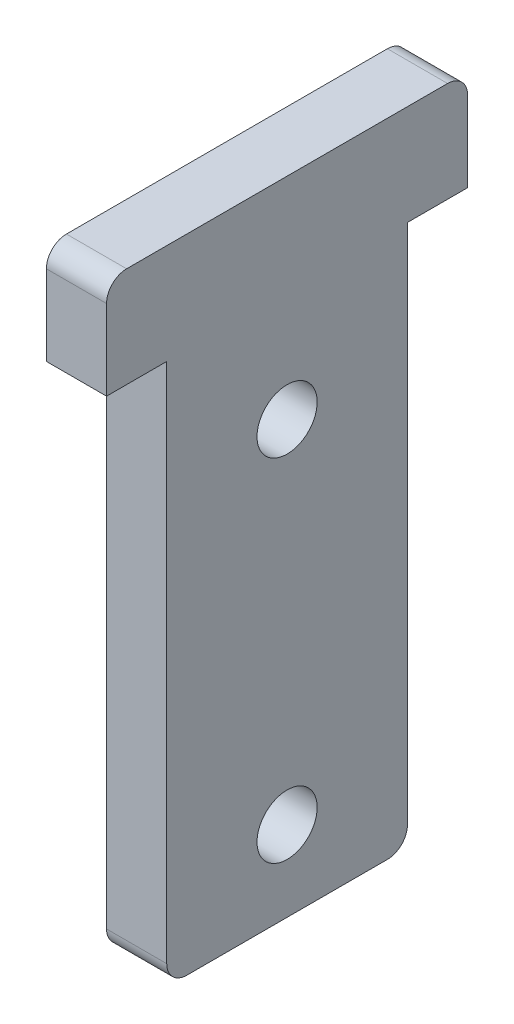
SolidWorks part; units mm, degrees
ref_plane "Front Plane" through (0, 0, 0) normal (0, 0, 1) x (1, 0, 0)
ref_plane "Top Plane" through (0, 0, 0) normal (0, 1, 0) x (1, 0, 0)
ref_plane "Right Plane" through (0, 0, 0) normal (1, 0, 0) x (0, 0, -1)
sketch "Sketch1" plane through (0, 0, 0) normal (1, 0, 0) x (0, 0, -1)
  line L1 (9, -16) -> (-9, -16)
  line L2 (9, -16) -> (9, 16)
  line L3 (9, 16) -> (-9, 16)
  line L4 (-9, -16) -> (-9, 16)
  line L5 (9, -16) -> (-9, 16) construction
  line L6 (9, 16) -> (-9, -16) construction
  point P0 (0, 0)
  dimension "D1" = 18
  dimension "D2" = 32
extrude "Boss-Extrude1" add sketch "Sketch1" along normal blind 3
sketch "Sketch2" plane through (3, 0, 0) normal (1, 0, 0) x (0, 0, -1)
  line L0 (6, -15) -> (6, 11)
  line L1 (-9, -16) -> (9, -16) construction
  line L2 (6, 11) -> (9, 11)
  line L3 (9, -16) -> (9, 16) construction
  line L4 (9, 11) -> (9, -16)
  line L5 (9, -16) -> (6, -16)
  line L6 (9, 16) -> (-9, 16) construction
  line L7 (5, -16) -> (-5, -16)
  line L8 (-6, -15) -> (-6, 11)
  line L9 (-6, 11) -> (-9, 11)
  line L10 (-9, 16) -> (-9, -16) construction
  line L11 (-9, 11) -> (-9, -16)
  line L12 (-9, -16) -> (-6, -16)
  line L13 (9, 11) -> (9, 15)
  line L14 (8, 16) -> (-8, 16)
  line L15 (-9, 15) -> (-9, 11)
  line L16 (-6, 11) -> (6, 11) construction
  line L17 (0, 11) -> (0, 5.5) construction
  line L18 (0, 5.5) -> (0, -12) construction
  arc A0 (5, -16) -> (6, -15) centre (5, -15) ccw
  arc A1 (-6, -15) -> (-5, -16) centre (-5, -15) ccw
  arc A2 (-8, 16) -> (-9, 15) centre (-8, 15) ccw
  arc A3 (9, 15) -> (8, 16) centre (8, 15) ccw
  circle A4 centre (0, 5.5) radius 1.5
  circle A5 centre (0, -12) radius 1.5
  point P30 (-9, 16)
  point P33 (9, 16)
  line M9 (-9, 16) -> (-9, -16)
  line M10 (-9, -16) -> (9, -16)
  line M11 (9, -16) -> (9, 16)
  line M12 (9, 16) -> (-9, 16)
  dimension "D2" = 1
  dimension "D3" = 1
  dimension "D8" = 1
  dimension "D9" = 1
  dimension "D11" = 3
  dimension "D13" = 3
  dimension "D1" = 5
  dimension "D4" = 3
  dimension "D5" = 3
  dimension "D6" = 12
  dimension "D7" = 32
  dimension "D10" = 5.5
  dimension "D12" = 17.5
extrude "Cut-Extrude2" cut sketch "Sketch2" against normal blind 3 contours A3 M11 M12 | A2 M12 M9 | A1 L8 L9 M9 M10 | A0 L2 L0 M10 M11 | A4 | A5
